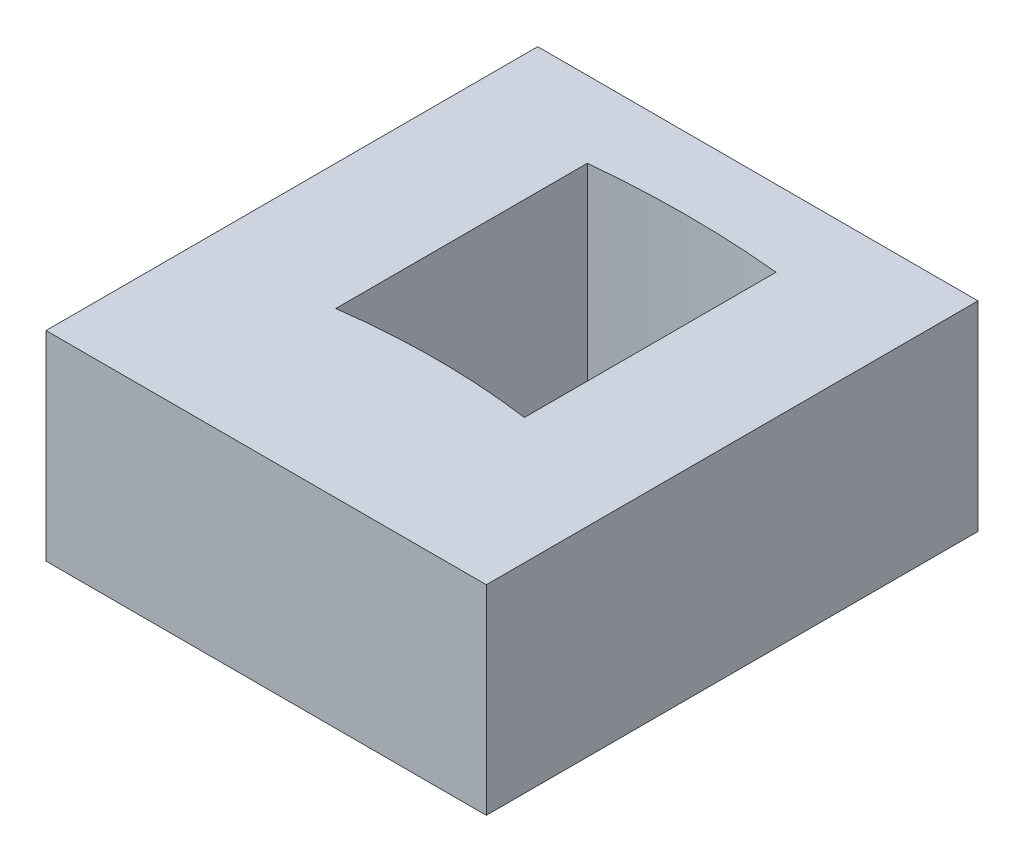
SolidWorks part; units mm, degrees
material "Copper"
ref_plane "Front" through (0, 0, 0) normal (0, 0, 1) x (1, 0, 0)
ref_plane "Top" through (0, 0, 0) normal (0, 1, 0) x (1, 0, 0)
ref_plane "Right" through (0, 0, 0) normal (1, 0, 0) x (0, 0, -1)
sketch "Sketch1" plane through (0, 0, 0) normal (0, 1, 0) x (1, 0, 0)
  line L0 (0, 0) -> (0, 4) construction
  line L2 (-1.6, 4) -> (-1.6, 0)
  line L3 (1.4, 4) -> (1.4, 0)
  line L4 (-3.6, 5.711) -> (-3.6, -2.6057)
  line L5 (3.4, 5.711) -> (3.4, -2.6057)
  line L6 (-3.6, 5.711) -> (3.4, 5.711)
  line L7 (-3.6, -2.6057) -> (3.4, -2.6057)
  line L8 (-3.6, 5.211) -> (3.4, 5.211)
  arc A1 (-1.6, 0) -> (1.4, 0) centre (-0.1, -10.8972) cw
  arc A2 (-1.6, 4) -> (1.4, 4) centre (-0.1, -10.9248) cw
  arc A5 (-3.6, -2.6057) -> (3.4, -2.6057) centre (-0.1, -10.8972) cw construction
  arc A7 (-3.6, 5.711) -> (3.4, 5.711) centre (-0.1, -10.9248) cw construction
  point P6 (0, 4)
  dimension "D1" = 4
  dimension "D2" = 11
  dimension "D4" = 15
  dimension "D6" = 0.5
  dimension "D3" = 3
  dimension "D5" = 2
extrude "Boss-Extrude1" add sketch "Sketch1" along normal blind 3.175 contours L8 L4 L7 L5 L2 A2 L3 A1
